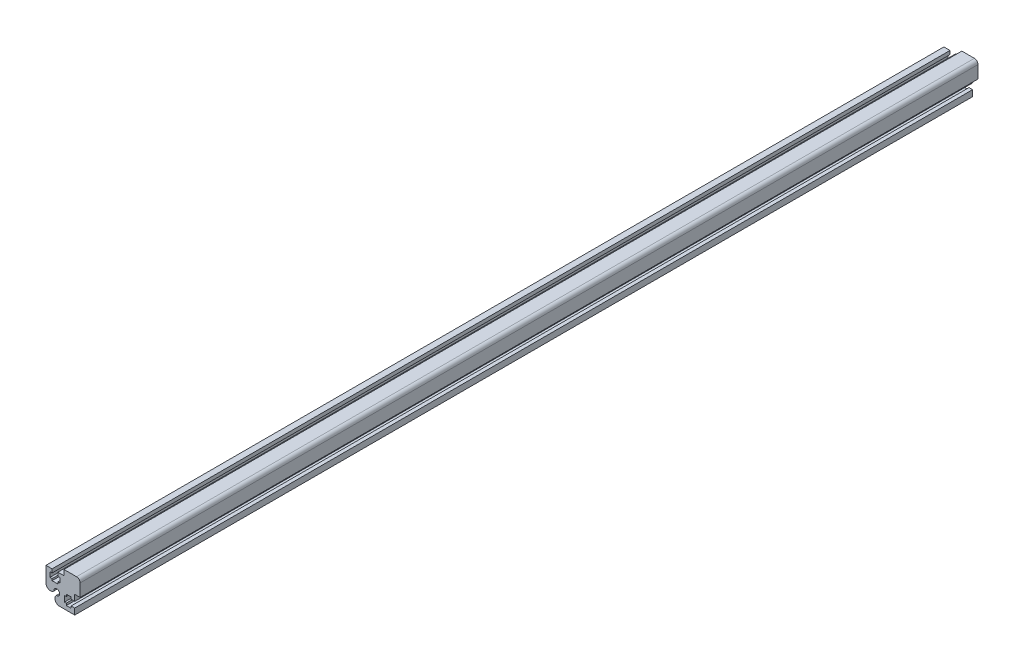
SolidWorks part; units mm, degrees
ref_plane "前视基准面" through (0, 0, 0) normal (0, 0, 1) x (1, 0, 0)
ref_plane "上视基准面" through (0, 0, 0) normal (0, 1, 0) x (1, 0, 0)
ref_plane "右视基准面" through (0, 0, 0) normal (1, 0, 0) x (0, 0, -1)
sketch "Model" plane through (0, 0, 0) normal (0, 0, 1) x (1, 0, 0)
  line L0 (13, 4) -> (10, 4)
  line L1 (-6, 1.4497) -> (-6, 10)
  line L2 (4, 10) -> (4, 13)
  line L3 (13, 11) -> (13, 4)
  line L4 (13, 4) -> (10, 4)
  line L5 (10, -6) -> (1.4497, -6)
  line L6 (11, 13) -> (4, 13)
  line L7 (4, 10) -> (0.6, 10)
  line L8 (0.6, 10) -> (0.6, 8)
  line L9 (0.6, 8) -> (1.75, 8)
  line L10 (1.75, 8) -> (1.75, 5.3)
  line L11 (1.75, 5.3) -> (0.6, 5.3)
  line L12 (-2.6, 5.3) -> (-3.75, 5.3)
  line L13 (-3.75, 5.3) -> (-3.75, 8)
  line L14 (-3.75, 8) -> (-2.6, 8)
  line L15 (-2.6, 8) -> (-2.6, 10)
  line L16 (-2.6, 10) -> (-6, 10)
  line L17 (10, 4) -> (10, 0.6)
  line L18 (10, 0.6) -> (8, 0.6)
  line L19 (8, 0.6) -> (8, 1.75)
  line L20 (8, 1.75) -> (5.3, 1.75)
  line L21 (5.3, 1.75) -> (5.3, 0.6)
  line L22 (5.3, -2.6) -> (5.3, -3.75)
  line L23 (5.3, -3.75) -> (8, -3.75)
  line L24 (8, -3.75) -> (8, -2.6)
  line L25 (8, -2.6) -> (10, -2.6)
  line L26 (10, -2.6) -> (10, -6)
  line L27 (-0.318, -1.7322) -> (-0.2209, -1.6351)
  line L28 (-1.7322, -0.318) -> (-1.6351, -0.2209)
  line L29 (0.6, 5.3) -> (0.6, 4.2903)
  line L30 (-2.6, 4.2903) -> (-2.6, 5.3)
  line L31 (-2.6, 4.2903) -> (0.6, 4.2903)
  line L32 (5.3, 0.6) -> (4.2903, 0.6)
  line L33 (4.2903, -2.6) -> (5.3, -2.6)
  line L34 (4.2903, -2.6) -> (4.2903, 0.6)
  line L35 (-1, 8) -> (-1, 10) construction
  line L36 (8, -1) -> (10, -1) construction
  arc A0 (13, 11) -> (11, 13) centre (11, 11) ccw
  arc A1 (-0.318, -1.7322) -> (1.4497, -6) centre (1.4497, -3.5) ccw
  arc A2 (-0.318, -1.7322) -> (1.4497, -6) centre (1.4497, -3.5) ccw
  arc A3 (-0.2209, -1.6351) -> (-1.6351, -0.2209) centre (0, 0) ccw
  arc A4 (-6, 1.4497) -> (-1.7322, -0.318) centre (-3.5, 1.4497) ccw
extrude "凸台-拉伸1" add sketch "Model" along normal blind 500 contours L1 A4 L28 A3 L27 A1 L5 L26 L25 L24 L23 L22 L33 L34 L32 L21 L20 L19 L18 L17 L0 L3 A0 L6 L2 L7 L8 L9 L10 L11 L29 L31 L30 L12 L13 L14 L15 L16
